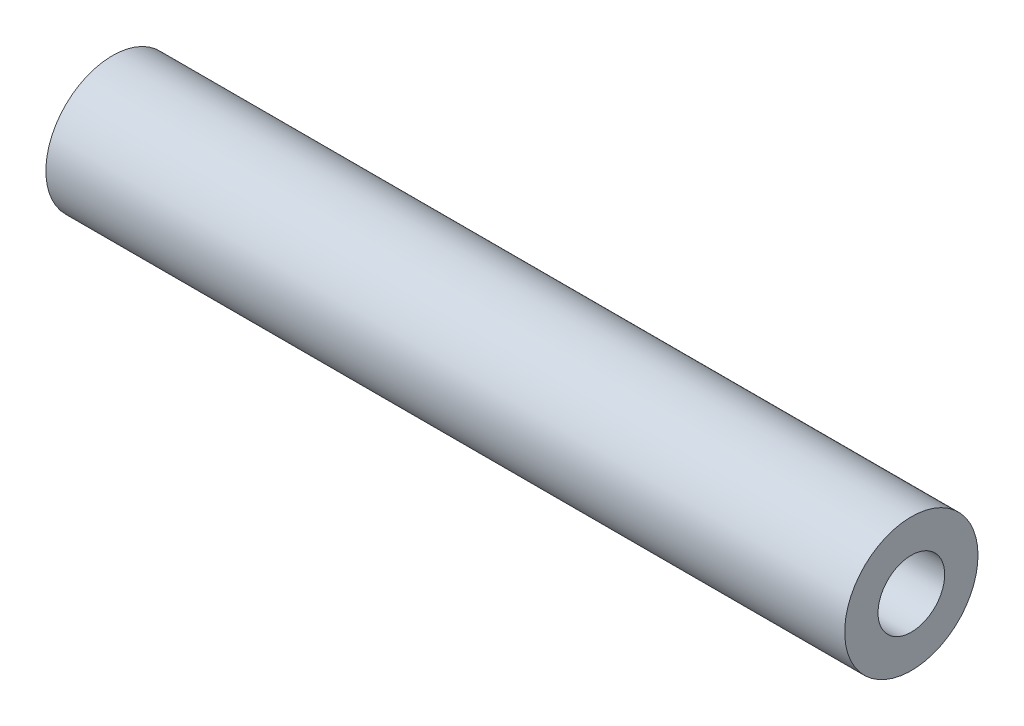
SolidWorks part; units mm, degrees
ref_plane "Piano frontale" through (0, 0, 0) normal (0, 0, 1) x (1, 0, 0)
ref_plane "Piano superiore" through (0, 0, 0) normal (0, 1, 0) x (1, 0, 0)
ref_plane "Piano destro" through (0, 0, 0) normal (1, 0, 0) x (0, 0, -1)
sketch "Schizzo2" plane through (0, 0, 0) normal (1, 0, 0) x (0, 0, -1)
  circle A0 centre (0, 0) radius 2.5
  circle A1 centre (0, 0) radius 1
  dimension "D1" = 5
  dimension "D2" = 2
extrude "Estrusione-Estrusione1" add sketch "Schizzo2" along normal mid plane 29.96
hole_wizard "Foro filettato M3x0.5-2" positions "Schizzo6" profile "Schizzo5" tap size "M3x0.5" standard "Ansi Metric"
sketch "Schizzo6" plane through (14.98, 0, 0) normal (1, 0, 0) x (0, 0, -1)
  point P0 (0, 0)
sketch "Schizzo5" plane through (14.98, 0, 0) normal (0, 1, 0) x (0, 0, -1)
  line L0 (0, 0) -> (0, 8.7511)
  line L1 (0, 8.7511) -> (1.25, 8)
  line L2 (1.25, 8) -> (1.25, 0)
  line L5 (1.25, 0) -> (0, 0)
  line L10 (0, 8.7511) -> (-1.25, 8) construction
  line L11 (0, -6.35) -> (0, 107.95) construction
  dimension "Tap Drill Dia." = 2.5
  dimension "Tap Drill Depth" = 8
  dimension "Drill Angle" = 118
mirror "Specchia1" about plane through (0, 0, 0) normal (1, 0, 0) of "Foro filettato M3x0.5-2"
